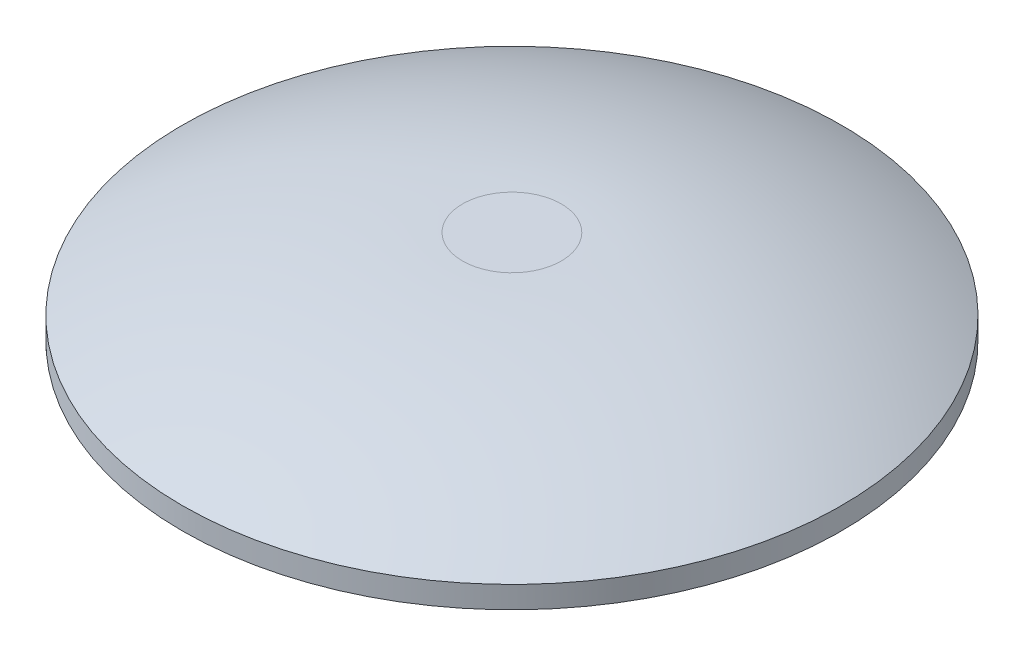
SolidWorks part; units mm, degrees
ref_plane "Front Plane" through (0, 0, 0) normal (0, 0, 1) x (1, 0, 0)
ref_plane "Top Plane" through (0, 0, 0) normal (0, 1, 0) x (1, 0, 0)
ref_plane "Right Plane" through (0, 0, 0) normal (1, 0, 0) x (0, 0, -1)
sketch "Sketch1" plane through (0, 0, 0) normal (0, 0, 1) x (1, 0, 0)
  line L0 (-45, 0) -> (45, 0) construction
  line L1 (300, -65.3534) -> (300, -85.3534)
  line L2 (-45, -150.7069) -> (45, -150.7069) construction
  line L3 (-45, 0) -> (-45, -150.7069) construction
  line L4 (45, 0) -> (45, -150.7069) construction
  line L5 (0, 0) -> (0, -150.7069)
  line L6 (45, 0) -> (0, 0)
  line L7 (0, -150.7069) -> (45, -150.7069)
  arc A0 (45, 0) -> (300, -65.3534) centre (45, -530.1639) cw
  arc A1 (-28.1177, 0) -> (35.3823, 0) centre (3.6323, -0.0236) cw construction
  arc A2 (45, -150.7069) -> (300, -85.3534) centre (45, 379.457) ccw
  point P4 (0, 0)
  dimension "D2" = 300
  dimension "D3" = 31.75
  dimension "D5" = 150.7069
  dimension "D1" = 90
  dimension "D4" = 20
revolve "Revolve1" add sketch "Sketch1" angle 360 about L5
